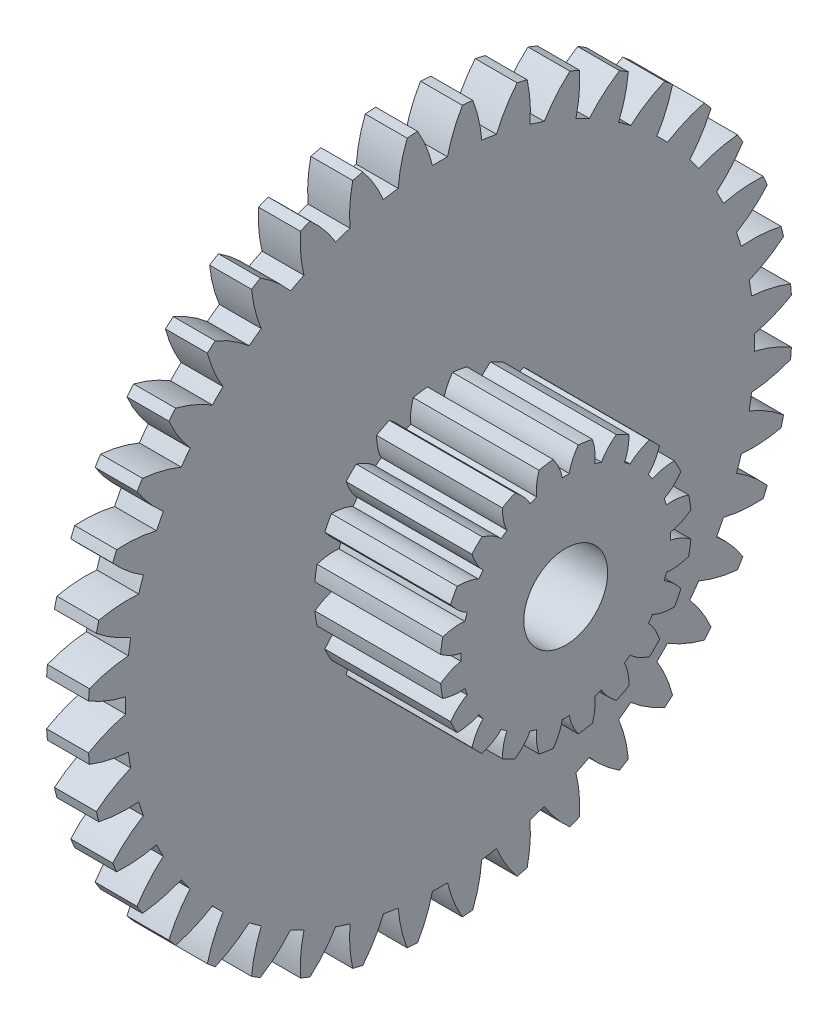
SolidWorks part; units mm, degrees
ref_plane "Plane1" through (0, 0, 0) normal (0, 0, 1) x (1, 0, 0)
ref_plane "Plane2" through (0, 0, 0) normal (0, 1, 0) x (1, 0, 0)
ref_plane "Plane3" through (0, 0, 0) normal (1, 0, 0) x (0, 0, -1)
sketch "HoldingSke" plane through (0, 0, 0) normal (0, 1, 0) x (1, 0, 0)
  line L0 (0, 0) -> (1.9151, -1.607)
  line L1 (-15, 0) -> (100, 0) construction
  line L2 (0, 0) -> (-2.1039, 2.3779)
  line L3 (0, 0) -> (-11.863, 4.5341)
  line L4 (0, 0) -> (6.6156, 5.5511)
  line L5 (0, 0) -> (-46.8476, -17.4728)
  line L6 (0, 0) -> (-0.829, -0.5593)
  line L7 (-2.1039, 2.3779) -> (8.6586, 51.2059)
  line L8 (-76.2, 54.61) -> (-75.9, 54.61)
  line L9 (-71.009, 38.7566) -> (-53.1078, 45.2721)
  line L10 (-76.2, 71.12) -> (104.1128, 71.12)
  line L11 (0, 0) -> (-1, 0)
  line L12 (-76.2, 101.6) -> (-76.185, 101.6)
  line L13 (24.9733, 27.94) -> (52.9518, 28.4284)
  line L14 (24.9733, 27.94) -> (24.9743, 27.94)
  line L15 (24.9733, 27.94) -> (100.4006, 29.5858)
  line L16 (-63.627, -0.4) -> (-12.827, -0.4)
  circle A0 centre (0, 0) radius 1
  circle A1 centre (0, 0) radius 7.499
  circle A2 centre (0, 0) radius 37.5
  circle A3 centre (0, 0) radius 1
  dimension "MHD" = 14.998
  dimension "Hub_dia" = 75
  dimension "Bore" = 2
  dimension "MBD" = 2
  dimension "Num_teeth" = 40
  dimension "Pitch" = 2.5
  dimension "Overall_len" = 50
  dimension "Show_teeth" = 40
  dimension "Thickness" = 1
  dimension "OAL" = 50.0001
  dimension "T_dim" = 0.3
  dimension "Ap" = 20
  dimension "H" = 19.05
  dimension "Pitch_radius" = 180.3128
  dimension "Width" = 1
  dimension "Backlash" = 0.015
  dimension "Addendum_fac" = 1
  dimension "Dedendum_fac" = 1.25
  dimension "Clearance_fac" = 0.25
  dimension "Dedendum_add" = 0.001
  dimension "Module" = 0.4
sketch "BasProSke" plane through (0, 0, 0) normal (0, 1, 0) x (1, 0, 0)
  line L0 (-10, 0) -> (60, 0) construction
  line L1 (0, 0) -> (0, 8.4)
  line L2 (0, 0) -> (1, 0)
  line L3 (1, 0) -> (1, 8.4)
  line L4 (1, 8.4) -> (0, 8.4)
  dimension "Thickness" = 1
  dimension "Diameter" = 16.8
revolve "Base-Revolve" add sketch "BasProSke" angle 360 about L0
sketch "TooCutSke" plane through (0, 0, 0) normal (1, 0, 0) x (0, 0, -1)
  line L1 (0, 0) -> (0, 107) construction
  line L2 (0, 0) -> (-0.3403, 7.9928) construction
  line L3 (0, 0) -> (-1.2545, 15.9404) construction
  line L4 (-0.3403, 7.9928) -> (-0.6273, 7.9702) construction
  arc A0 (0.179, 7.4969) -> (-0.179, 7.4969) centre (0, 0) ccw
  arc A1 (0.5503, 8.4074) -> (-0.5503, 8.4074) centre (0, 0) ccw
  circle A2 centre (0, 0) radius 8 construction
  circle A3 centre (0, 0) radius 7.5175 construction
  arc A4 (-0.179, 7.4969) -> (-0.5503, 8.4074) centre (-3.2926, 6.7581) ccw
  arc A5 (0.5503, 8.4074) -> (0.179, 7.4969) centre (3.2926, 6.7581) ccw
  dimension "Root_dia" = 14.998
  dimension "Overcut_dia" = 16.8508
  dimension "Pitch_dia" = 16
  dimension "Base_dia" = 15.0351
  dimension "Flank_rad" = 3.2
  dimension "Half_ang" = 4.5
  dimension "Half_CT" = 0.2878
extrude "ToothCut" cut sketch "TooCutSke" along normal through all
fillet "Breaks" [suppressed] radius 0.008
fillet "RootFillets" [suppressed] radius 0.101
pattern_circular "TeethCuts" count 40 every 9 about axis through (-10, 0, 0) along (1, 0, 0) of "ToothCut", "RootFillets", "Breaks"
sketch "HubNeaOneSke" plane through (0, 0, 0) normal (-1, 0, 0) x (0, 0, 1)
  circle A0 centre (0, 0) radius 7.499
  dimension "Diameter" = 14.998
extrude "HubNearOne" [suppressed] add sketch "HubNeaOneSke" along normal blind 49.0001
sketch "HubNeaBotSke" plane through (0, 0, 0) normal (-1, 0, 0) x (0, 0, 1)
  circle A0 centre (0, 0) radius 7.499
  dimension "Diameter" = 14.998
extrude "HubNearBoth" [suppressed] add sketch "HubNeaBotSke" along normal blind 24.5
ref_plane "FarPln" through (1, 0, 0) normal (1, 0, 0) x (0, 0, -1)
sketch "HubFarSke" plane through (1, 0, 0) normal (1, 0, 0) x (0, 0, -1)
  circle A0 centre (0, 0) radius 7.499
  dimension "Diameter" = 14.998
extrude "HubFar" [suppressed] add sketch "HubFarSke" along normal blind 24.5
sketch "BorSke" plane through (0, 0, 0) normal (1, 0, 0) x (0, 0, -1)
  circle A0 centre (0, 0) radius 1
  dimension "Diameter" = 2
extrude "Bore" cut sketch "BorSke" along normal mid plane 100.0001
sketch "KeySke" plane through (0, 0, 0) normal (1, 0, 0) x (0, 0, -1)
  line L0 (-0.4, 0) -> (-0.4, 1.3)
  line L1 (-0.4, 1.3) -> (0.4, 1.3)
  line L2 (0.4, 1.3) -> (0.4, 0)
  line L3 (0, 0) -> (0, 34) construction
  line L4 (-0.4, 0) -> (0.4, 0)
  dimension "Offset" = 1.3
  dimension "Width" = 0.8
extrude "Keyway" [suppressed] cut sketch "KeySke" along normal mid plane 100.0001
pattern_circular "Keyway2" [suppressed] count 2 every 90 about axis through (-10, 0, 0) along (1, 0, 0)
sketch "Schizzo2" plane through (0, 0, 0) normal (1, 0, 0) x (0, 0, -1)
  circle A0 centre (0, 0) radius 3
  circle A1 centre (0, 0) radius 1
  circle A6 centre (0, 0) radius 1 construction
  dimension "D1" = 6
extrude "Estrusione-Estrusione1" add sketch "Schizzo2" along normal blind 3 from surface at 1 starting at face at (1, 0, 1)
sketch "Schizzo3" plane through (4, 0, 0) normal (1, 0, 0) x (0, 0, -1)
  line L0 (0, 0) -> (5.6071, 0) construction
  line L1 (0, 0) -> (2.4985, 0.0872) construction
  line L2 (0, 0) -> (2.4985, -0.0872) construction
  line L3 (3.706, -1.13) -> (3.706, 1.13)
  arc A0 (2.4985, -0.0872) -> (2.4985, 0.0872) centre (0, 0) ccw
  spline S0 degree 4 poles (2.4985, 0.0872) (2.5009, 0.0873) (2.5077, 0.0877) (2.5206, 0.0892) (2.5414, 0.0924) (2.5798, 0.1004) (2.6253, 0.1133) (2.6758, 0.131) (2.7292, 0.1532) (2.7741, 0.174) (2.8182, 0.1965) (2.8615, 0.2205) (2.9131, 0.2514) (2.9738, 0.2909) (3.0428, 0.3406) (3.1187, 0.401) (3.1932, 0.4669) (3.2642, 0.5351) (3.3331, 0.6077) (3.3976, 0.6806) (3.4615, 0.76) (3.5188, 0.8351) (3.5792, 0.9229) (3.627, 0.9949) (3.6858, 1.0937) (3.7193, 1.1531) (3.757, 1.2239) (3.7729, 1.256) (3.7828, 1.2757) knots 0 0 0 0 0 0.005377 0.015084 0.028532 0.04661 0.092111 0.119476 0.146842 0.174209 0.201575 0.228941 0.256307 0.307035 0.361767 0.4165 0.471232 0.525964 0.580697 0.635429 0.690161 0.744894 0.799626 0.854358 0.909091 0.954545 1 1 1 1 1 construction
  spline S1 degree 4 poles (2.4985, 0.0872) (2.5009, 0.0873) (2.5077, 0.0877) (2.5206, 0.0892) (2.5414, 0.0924) (2.5798, 0.1004) (2.6253, 0.1133) (2.6758, 0.131) (2.7292, 0.1532) (2.7741, 0.174) (2.8182, 0.1965) (2.8615, 0.2205) (2.9131, 0.2514) (2.9738, 0.2909) (3.0428, 0.3406) (3.1187, 0.401) (3.1932, 0.4669) (3.2642, 0.5351) (3.3331, 0.6077) (3.3976, 0.6806) (3.4615, 0.76) (3.5188, 0.8351) (3.5792, 0.9229) (3.627, 0.9949) (3.673, 1.0723) (3.695, 1.1104) (3.706, 1.13) knots 0 0 0 0 0 0.005377 0.015084 0.028532 0.04661 0.092111 0.119476 0.146842 0.174209 0.201575 0.228941 0.256307 0.307035 0.361767 0.4165 0.471232 0.525964 0.580697 0.635429 0.690161 0.744894 0.799626 0.854358 0.909091 0.909091 0.909091 0.909091 0.909091
  spline S2 degree 4 poles (2.4985, -0.0872) (2.5009, -0.0873) (2.5077, -0.0877) (2.5206, -0.0892) (2.5414, -0.0924) (2.5798, -0.1004) (2.6253, -0.1133) (2.6758, -0.131) (2.7292, -0.1532) (2.7741, -0.174) (2.8182, -0.1965) (2.8615, -0.2205) (2.9131, -0.2514) (2.9738, -0.2909) (3.0428, -0.3406) (3.1187, -0.401) (3.1932, -0.4669) (3.2642, -0.5351) (3.3331, -0.6077) (3.3976, -0.6806) (3.4615, -0.76) (3.5188, -0.8351) (3.5792, -0.9229) (3.627, -0.9949) (3.673, -1.0723) (3.695, -1.1104) (3.706, -1.13) knots 0 0 0 0 0 0.005377 0.015084 0.028532 0.04661 0.092111 0.119476 0.146842 0.174209 0.201575 0.228941 0.256307 0.307035 0.361767 0.4165 0.471232 0.525964 0.580697 0.635429 0.690161 0.744894 0.799626 0.854358 0.909091 0.909091 0.909091 0.909091 0.909091
  dimension "D1" = 5
  dimension "D2" = 2
  dimension "D3" = 178
extrude "Taglio-Estrusione1" cut sketch "Schizzo3" against normal up to surface (3 mm away) up to face at (1, 0, 3)
pattern_circular "RipetizioneCircolare1" count 20 over 360 about axis through (50.0001, 0, 0) along (-1, 0, 0) of "Taglio-Estrusione1"
equation "' \"Module@HoldingSke\" = 6.35"
equation "' \"Num_teeth@HoldingSke\" = 12"
equation "' \"Ap@HoldingSke\" =  20"
equation "' \"Ap@HoldingSke\" = 20"
equation "' \"Width@HoldingSke\" = 0.5 * 25.4"
equation "' \"Hub_dia@HoldingSke\"= 1 * 25.4"
equation "' \"Hub_dia@HoldingSke\" = 1 * 25.4"
equation "' \"Overall_len@HoldingSke\" = 1.0 * 25.4"
equation "' \"Bore@HoldingSke\" = 0.75 * 25.4"
equation "' \"T_dim@HoldingSke\" = 0.1 * 25.4"
equation "' \"Width@KeySke\" = 0.25 * 25.4"
equation "' \"Show_teeth@HoldingSke\" = 13"
equation "' \"Backlash@HoldingSke\" = 0.009 * 25.4"
equation "' \"Addendum_fac@HoldingSke\" = 1.0"
equation "' \"Dedendum_fac@HoldingSke\" = 1.25"
equation "' \"Dedendum_add@HoldingSke\" = 0.00005 * 25.4"
equation "' \"Clearance_fac@HoldingSke\" = 0.25"
equation "\"Pitch@HoldingSke\" = 1 / \"Module@HoldingSke\""
equation "\"Overcut_dia@TooCutSke\" = (\"Num_teeth@HoldingSke\" + 2 * \"Addendum_fac@HoldingSke\") / \"Pitch@HoldingSke\" + 0.002 * 25.4"
equation "\"Pitch_dia@TooCutSke\" = \"Num_teeth@HoldingSke\" / \"Pitch@HoldingSke\""
equation "\"Base_dia@TooCutSke\" = \"Num_teeth@HoldingSke\" / \"Pitch@HoldingSke\" * cos((\"Ap@HoldingSke\"  * 3.14159265 / 180))"
equation "\"Root_dia@TooCutSke\" = (\"Num_teeth@HoldingSke\" + 2) / \"Pitch@HoldingSke\" - 2 * (\"Addendum_fac@HoldingSke\" + \"Dedendum_fac@HoldingSke\") / \"Pitch@HoldingSke\" - \"Dedendum_add@HoldingSke\" * 2"
equation "\"Half_ang@TooCutSke\" = 180 / \"Num_teeth@HoldingSke\""
equation "\"Half_CT@TooCutSke\" = \"Num_teeth@HoldingSke\" / \"Pitch@HoldingSke\" * sin((3.14159265 / 2 / \"Num_teeth@HoldingSke\")) / 2 - 7 * \"Backlash@HoldingSke\" / 4"
equation "\"Flank_rad@TooCutSke\" = \"Num_teeth@HoldingSke\" / \"Pitch@HoldingSke\" / 5"
equation "\"Radius@RootFillets\" = \"Clearance_fac@HoldingSke\" / \"Pitch@HoldingSke\" + \"Dedendum_add@HoldingSke\""
equation "\"Break_rad@Breaks\" = 0.02 / \"Pitch@HoldingSke\""
equation "\"Thickness@HoldingSke\" = \"Width@HoldingSke\""
equation "\"OAL@HoldingSke\" = \"Thickness@HoldingSke\""
equation "\"MHD@HoldingSke\" = (\"Num_teeth@HoldingSke\" + 2) / \"Pitch@HoldingSke\" - 2 * (\"Addendum_fac@HoldingSke\" + \"Dedendum_fac@HoldingSke\")  / \"Pitch@HoldingSke\" - \"Dedendum_add@HoldingSke\" * 2"
equation "\"MBD@HoldingSke\" = (\"Num_teeth@HoldingSke\" + 2) / \"Pitch@HoldingSke\" - 2 * (\"Addendum_fac@HoldingSke\" + \"Dedendum_fac@HoldingSke\")  / \"Pitch@HoldingSke\" - \"Dedendum_add@HoldingSke\" * 2 - 0.002 * 25.4"
equation "\"MHD@HoldingSke\" = ((sgn( \"MHD@HoldingSke\" - \"Hub_dia@HoldingSke\" )-1)*( \"MHD@HoldingSke\" - \"Hub_dia@HoldingSke\" ))/-2+ \"Hub_dia@HoldingSke\""
equation "\"MBD@HoldingSke\" = ((sgn( \"MBD@HoldingSke\" - \"Bore@HoldingSke\" )-1)*( \"MBD@HoldingSke\" - \"Bore@HoldingSke\" ))/-2+ \"Bore@HoldingSke\""
equation "\"OAL@HoldingSke\" = ((sgn( \"OAL@HoldingSke\" - \"Overall_len@HoldingSke\" )+1)*( \"OAL@HoldingSke\" - \"Overall_len@HoldingSke\" ))/2 + \"Overall_len@HoldingSke\" + 0.000002 * 25.4"
equation "\"Num_teeth@TeethCuts\" = int( \"Show_teeth@HoldingSke\" ) + 1"
equation "\"Num_teeth@TeethCuts\" = ((sgn( \"Num_teeth@TeethCuts\" - \"Num_teeth@HoldingSke\" )-1)*( \"Num_teeth@TeethCuts\" - \"Num_teeth@HoldingSke\" ))/-2+ \"Num_teeth@HoldingSke\""
equation "\"Num_teeth@TeethCuts\" = ((sgn( \"Num_teeth@TeethCuts\" - 2.0)+1)*( \"Num_teeth@TeethCuts\" - 2.0))/2 +2.0"
equation "\"Angle@TeethCuts\" = 360.0 / \"Num_teeth@HoldingSke\""
equation "\"Diameter@BasProSke\" = (\"Num_teeth@HoldingSke\" + 2 * \"Addendum_fac@HoldingSke\") / \"Pitch@HoldingSke\""
equation "\"Thickness@BasProSke\"  = \"Thickness@HoldingSke\""
equation "' \"Fillet_rad@BasProSke\" =  \"Thickness@HoldingSke\" * 0.05"
equation "' \"Fillet_rad@BasProSke\" = \"Thickness@HoldingSke\" * 0.05"
equation "\"MHD@HoldingSke\" = ((sgn( \"MHD@HoldingSke\" - \"Root_dia@TooCutSke\" )-1)*( \"MHD@HoldingSke\" - \"Root_dia@TooCutSke\" ))/-2+ \"Root_dia@TooCutSke\""
equation "\"Diameter@HubNeaOneSke\" = \"MHD@HoldingSke\""
equation "\"Length@HubNearOne\" = \"OAL@HoldingSke\" - \"Thickness@BasProSke\""
equation "\"Diameter@HubNeaBotSke\" = \"MHD@HoldingSke\""
equation "\"Length@HubNearBoth\" = ( \"OAL@HoldingSke\" - \"Thickness@BasProSke\" ) / 2.0"
equation "\"Thickness@FarPln\" = \"Thickness@BasProSke\""
equation "\"Diameter@HubFarSke\" = \"MHD@HoldingSke\""
equation "\"Length@HubFar\" = ( \"OAL@HoldingSke\" - \"Thickness@BasProSke\" ) / 2.0"
equation "\"Diameter@BorSke\" = \"MBD@HoldingSke\""
equation "\"D1@Bore\" = \"OAL@HoldingSke\" * 2.0"
equation "\"D1@Keyway\" = \"OAL@HoldingSke\" * 2.0"
equation "\"Offset@KeySke\" = \"T_dim@HoldingSke\" + \"MBD@HoldingSke\" / 2.0"
